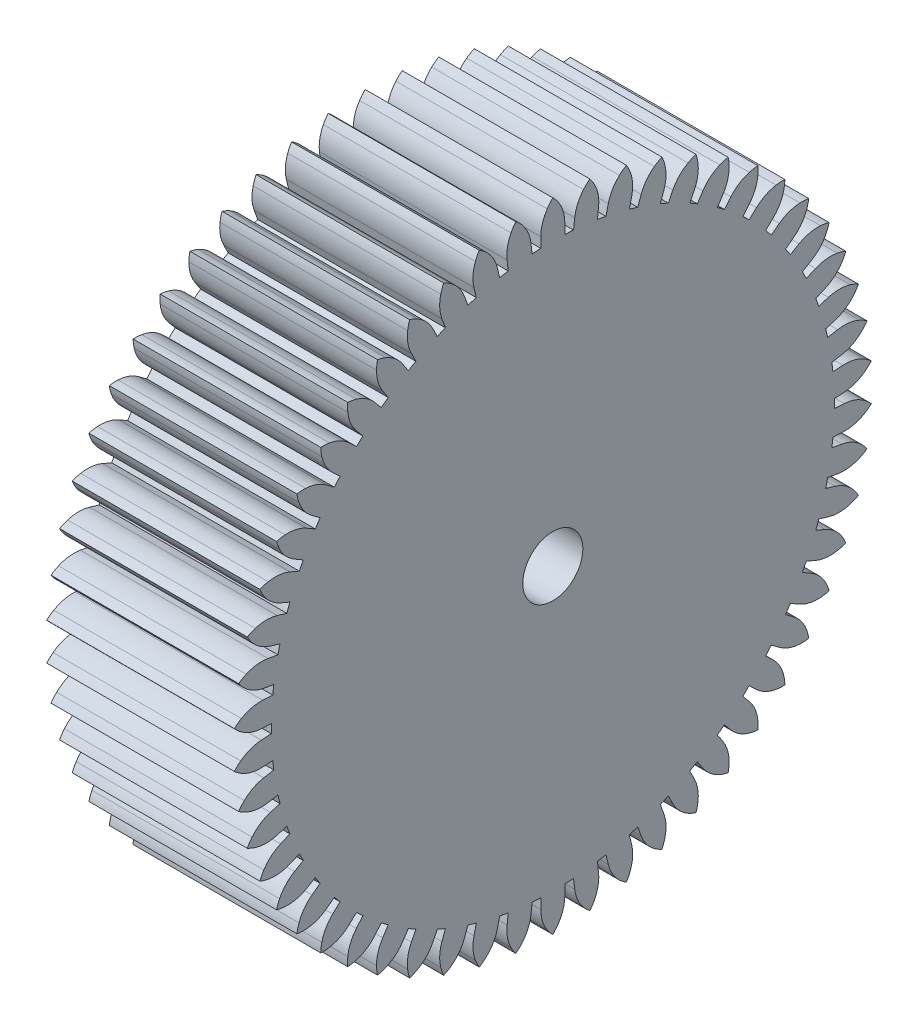
SolidWorks part; units mm, degrees
ref_plane "Front Plane" through (0, 0, 0) normal (0, 0, 1) x (1, 0, 0)
ref_plane "Top Plane" through (0, 0, 0) normal (0, 1, 0) x (1, 0, 0)
ref_plane "Right Plane" through (0, 0, 0) normal (1, 0, 0) x (0, 0, -1)
sketch "Sketch1" plane through (0, 0, 0) normal (1, 0, 0) x (0, 0, -1)
  line L0 (-0.64, 14.9863) -> (-0.64, 15.5242)
  line L1 (0, 18.7) -> (0, -18.7) construction
  line L2 (0, 17) -> (0, 15)
  line L3 (0.64, 14.9863) -> (0.64, 15.5242)
  line L4 (1.1041, 14.9593) -> (1.1666, 15.4936)
  line L5 (2.3755, 14.8107) -> (2.4379, 15.345)
  line L6 (2.8333, 14.73) -> (2.9574, 15.2534)
  line L7 (4.0788, 14.4348) -> (4.2029, 14.9582)
  line L8 (4.5242, 14.3014) -> (4.7082, 14.8069)
  line L9 (5.727, 13.8637) -> (5.911, 14.3691)
  line L10 (6.1539, 13.6795) -> (6.3953, 14.1602)
  line L11 (7.2978, 13.1051) -> (7.5392, 13.5857)
  line L12 (7.7004, 12.8726) -> (7.996, 13.322)
  line L13 (8.7698, 12.1692) -> (9.0654, 12.6186)
  line L14 (9.1428, 11.8916) -> (9.4885, 12.3036)
  line L15 (10.1233, 11.0688) -> (10.469, 11.4809)
  line L16 (10.4615, 10.7498) -> (10.8527, 11.1189)
  line L17 (11.3399, 9.8187) -> (11.7311, 10.1878)
  line L18 (11.6387, 9.4626) -> (12.0702, 9.7838)
  line L19 (12.4031, 8.4359) -> (12.8345, 8.7571)
  line L20 (12.6586, 8.0474) -> (13.1244, 8.3164)
  line L21 (13.2986, 6.9389) -> (13.7644, 7.2079)
  line L22 (13.5072, 6.5234) -> (14.0011, 6.7365)
  line L23 (14.0142, 5.3481) -> (14.5081, 5.5612)
  line L24 (14.1732, 4.9112) -> (14.6885, 5.0655)
  line L25 (14.5403, 3.685) -> (15.0556, 3.8393)
  line L26 (14.6475, 3.2326) -> (15.1772, 3.326)
  line L27 (14.8698, 1.9721) -> (15.3995, 2.0655)
  line L28 (14.9238, 1.5103) -> (15.4607, 1.5416)
  line L29 (14.9982, 0.2325) -> (15.5352, 0.2637)
  line L30 (14.9982, -0.2325) -> (15.5352, -0.2637)
  line L31 (14.9238, -1.5103) -> (15.4607, -1.5416)
  line L32 (14.8698, -1.9721) -> (15.3995, -2.0655)
  line L33 (14.6475, -3.2326) -> (15.1772, -3.326)
  line L34 (14.5403, -3.685) -> (15.0556, -3.8393)
  line L35 (14.1732, -4.9112) -> (14.6885, -5.0655)
  line L36 (14.0142, -5.3481) -> (14.5081, -5.5612)
  line L37 (13.5072, -6.5234) -> (14.0011, -6.7365)
  line L38 (13.2986, -6.9389) -> (13.7644, -7.2079)
  line L39 (12.6586, -8.0474) -> (13.1244, -8.3164)
  line L40 (12.4031, -8.4359) -> (12.8345, -8.7571)
  line L41 (11.6387, -9.4626) -> (12.0702, -9.7838)
  line L42 (11.3399, -9.8187) -> (11.7311, -10.1878)
  line L43 (10.4615, -10.7498) -> (10.8527, -11.1189)
  line L44 (10.1233, -11.0688) -> (10.469, -11.4809)
  line L45 (9.1428, -11.8916) -> (9.4885, -12.3036)
  line L46 (8.7698, -12.1692) -> (9.0654, -12.6186)
  line L47 (7.7004, -12.8726) -> (7.996, -13.322)
  line L48 (7.2978, -13.1051) -> (7.5392, -13.5857)
  line L49 (6.1539, -13.6795) -> (6.3953, -14.1602)
  line L50 (5.727, -13.8637) -> (5.911, -14.3691)
  line L51 (4.5242, -14.3014) -> (4.7082, -14.8069)
  line L52 (4.0788, -14.4348) -> (4.2029, -14.9582)
  line L53 (2.8333, -14.73) -> (2.9574, -15.2534)
  line L54 (2.3755, -14.8107) -> (2.4379, -15.345)
  line L55 (1.1041, -14.9593) -> (1.1666, -15.4936)
  line L56 (0.64, -14.9863) -> (0.64, -15.5242)
  line L57 (-0.64, -14.9863) -> (-0.64, -15.5242)
  line L58 (-1.1041, -14.9593) -> (-1.1666, -15.4936)
  line L59 (-2.3755, -14.8107) -> (-2.4379, -15.345)
  line L60 (-2.8333, -14.73) -> (-2.9574, -15.2534)
  line L61 (-4.0788, -14.4348) -> (-4.2029, -14.9582)
  line L62 (-4.5242, -14.3014) -> (-4.7082, -14.8069)
  line L63 (-5.727, -13.8637) -> (-5.911, -14.3691)
  line L64 (-6.1539, -13.6795) -> (-6.3953, -14.1602)
  line L65 (-7.2978, -13.1051) -> (-7.5392, -13.5857)
  line L66 (-7.7004, -12.8726) -> (-7.996, -13.322)
  line L67 (-8.7698, -12.1692) -> (-9.0654, -12.6186)
  line L68 (-9.1428, -11.8916) -> (-9.4885, -12.3036)
  line L69 (-10.1233, -11.0688) -> (-10.469, -11.4809)
  line L70 (-10.4615, -10.7498) -> (-10.8527, -11.1189)
  line L71 (-11.3399, -9.8187) -> (-11.7311, -10.1878)
  line L72 (-11.6387, -9.4626) -> (-12.0702, -9.7838)
  line L73 (-12.4031, -8.4359) -> (-12.8345, -8.7571)
  line L74 (-12.6586, -8.0474) -> (-13.1244, -8.3164)
  line L75 (-13.2986, -6.9389) -> (-13.7644, -7.2079)
  line L76 (-13.5072, -6.5234) -> (-14.0011, -6.7365)
  line L77 (-14.0142, -5.3481) -> (-14.5081, -5.5612)
  line L78 (-14.1732, -4.9112) -> (-14.6885, -5.0655)
  line L79 (-14.5403, -3.685) -> (-15.0556, -3.8393)
  line L80 (-14.6475, -3.2326) -> (-15.1772, -3.326)
  line L81 (-14.8698, -1.9721) -> (-15.3995, -2.0655)
  line L82 (-14.9238, -1.5103) -> (-15.4607, -1.5416)
  line L83 (-14.9982, -0.2325) -> (-15.5352, -0.2637)
  line L84 (-14.9982, 0.2325) -> (-15.5352, 0.2637)
  line L85 (-14.9238, 1.5103) -> (-15.4607, 1.5416)
  line L86 (-14.8698, 1.9721) -> (-15.3995, 2.0655)
  line L87 (-14.6475, 3.2326) -> (-15.1772, 3.326)
  line L88 (-14.5403, 3.685) -> (-15.0556, 3.8393)
  line L89 (-14.1732, 4.9112) -> (-14.6885, 5.0655)
  line L90 (-14.0142, 5.3481) -> (-14.5081, 5.5612)
  line L91 (-13.5072, 6.5234) -> (-14.0011, 6.7365)
  line L92 (-13.2986, 6.9389) -> (-13.7644, 7.2079)
  line L93 (-12.6586, 8.0474) -> (-13.1244, 8.3164)
  line L94 (-12.4031, 8.4359) -> (-12.8345, 8.7571)
  line L95 (-11.6387, 9.4626) -> (-12.0702, 9.7838)
  line L96 (-11.3399, 9.8187) -> (-11.7311, 10.1878)
  line L97 (-10.4615, 10.7498) -> (-10.8527, 11.1189)
  line L98 (-10.1233, 11.0688) -> (-10.469, 11.4809)
  line L99 (-9.1428, 11.8916) -> (-9.4885, 12.3036)
  line L100 (-8.7698, 12.1692) -> (-9.0654, 12.6186)
  line L101 (-7.7004, 12.8726) -> (-7.996, 13.322)
  line L102 (-7.2978, 13.1051) -> (-7.5392, 13.5857)
  line L103 (-6.1539, 13.6795) -> (-6.3953, 14.1602)
  line L104 (-5.727, 13.8637) -> (-5.911, 14.3691)
  line L105 (-4.5242, 14.3014) -> (-4.7082, 14.8069)
  line L106 (-4.0788, 14.4348) -> (-4.2029, 14.9582)
  line L107 (-2.8333, 14.73) -> (-2.9574, 15.2534)
  line L108 (-2.3755, 14.8107) -> (-2.4379, 15.345)
  line L109 (-1.1041, 14.9593) -> (-1.1666, 15.4936)
  arc A0 (-0.64, 14.9863) -> (-1.1041, 14.9593) centre (0, 0) ccw
  arc A2 (-0.64, 15.5242) -> (-0.2982, 16.6425) centre (1.36, 15.5242) cw
  arc A3 (-0.2982, 16.6425) -> (0, 17) centre (1.6012, 15.3616) cw
  arc A4 (0.64, 15.5242) -> (0.2982, 16.6425) centre (-1.36, 15.5242) ccw
  arc A5 (0.2982, 16.6425) -> (0, 17) centre (-1.6012, 15.3616) ccw
  arc A6 (2.4379, 15.345) -> (2.2282, 16.4953) centre (0.4514, 15.5771) ccw
  arc A7 (2.2282, 16.4953) -> (1.9736, 16.8851) centre (0.193, 15.4436) ccw
  arc A8 (1.6359, 16.5646) -> (1.9736, 16.8851) centre (3.3737, 15.0718) cw
  arc A9 (1.1666, 15.4936) -> (1.6359, 16.5646) centre (3.1531, 15.2614) cw
  arc A10 (4.2029, 14.9582) -> (4.1281, 16.1251) centre (2.2568, 15.4194) ccw
  arc A11 (4.1281, 16.1251) -> (3.9205, 16.5418) centre (1.9846, 15.3168) ccw
  arc A12 (3.5479, 16.2626) -> (3.9205, 16.5418) centre (5.1006, 14.5783) cw
  arc A13 (2.9574, 15.2534) -> (3.5479, 16.2626) centre (4.9035, 14.7921) cw
  arc A14 (5.911, 14.3691) -> (5.9722, 15.5368) centre (4.0316, 15.0531) ccw
  arc A15 (5.9722, 15.5368) -> (5.8143, 15.9748) centre (3.7494, 14.9828) ccw
  arc A16 (5.4119, 15.7408) -> (5.8143, 15.9748) centre (6.7586, 13.8875) cw
  arc A17 (4.7082, 14.8069) -> (5.4119, 15.7408) centre (6.5876, 14.1228) cw
  arc A18 (7.5392, 13.5857) -> (7.7356, 14.7384) centre (5.7519, 14.4833) ccw
  arc A19 (7.7356, 14.7384) -> (7.6296, 15.1918) centre (5.4634, 14.4462) ccw
  arc A20 (7.2027, 15.0061) -> (7.6296, 15.1918) centre (8.3251, 13.009) cw
  arc A21 (6.3953, 14.1602) -> (7.2027, 15.0061) centre (8.1826, 13.2626) cw
  arc A22 (9.0654, 12.6186) -> (9.3943, 13.7407) centre (7.3944, 13.7176) ccw
  arc A23 (9.3943, 13.7407) -> (9.3417, 14.2033) centre (7.1036, 13.7143) ccw
  arc A24 (8.8961, 14.0684) -> (9.3417, 14.2033) centre (9.7791, 11.9546) cw
  arc A25 (7.996, 13.322) -> (8.8961, 14.0684) centre (9.667, 12.223) cw
  arc A26 (10.469, 11.4809) -> (10.926, 12.5572) centre (8.937, 12.7664) ccw
  arc A27 (10.926, 12.5572) -> (10.9274, 13.0228) centre (8.6477, 12.7969) ccw
  arc A28 (10.4692, 12.9405) -> (10.9274, 13.0228) centre (11.1008, 10.7384) cw
  arc A29 (9.4885, 12.3036) -> (10.4692, 12.9405) centre (11.0206, 11.0181) cw
  arc A30 (11.7311, 10.1878) -> (12.3099, 11.2039) centre (10.3586, 11.6426) ccw
  arc A31 (12.3099, 11.2039) -> (12.3654, 11.6661) centre (10.0748, 11.7064) ccw
  arc A32 (11.9007, 11.6376) -> (12.3654, 11.6661) centre (12.2724, 9.3771) cw
  arc A33 (10.8527, 11.1189) -> (11.9007, 11.6376) centre (12.2252, 9.6641) cw
  arc A34 (12.8345, 8.7571) -> (13.5274, 9.699) centre (11.6402, 10.3613) ccw
  arc A35 (13.5274, 9.699) -> (13.6361, 10.1517) centre (11.3657, 10.4576) ccw
  arc A36 (13.1713, 10.1774) -> (13.6361, 10.1517) centre (13.278, 7.889) cw
  arc A37 (12.0702, 9.7838) -> (13.1713, 10.1774) centre (13.2645, 8.1795) cw
  arc A38 (13.7644, 7.2079) -> (14.5619, 8.063) centre (12.7644, 8.9399) ccw
  arc A39 (14.5619, 8.063) -> (14.7224, 8.5) centre (12.5029, 9.0674) ccw
  arc A40 (14.2637, 8.5795) -> (14.7224, 8.5) centre (14.1041, 6.2941) cw
  arc A41 (13.1244, 8.3164) -> (14.2637, 8.5795) centre (14.1244, 6.5843) cw
  arc A42 (14.5081, 5.5612) -> (15.3995, 6.318) centre (13.7159, 7.3976) ccw
  arc A43 (15.3995, 6.318) -> (15.6097, 6.7334) centre (13.4711, 7.5546) ccw
  arc A44 (15.1633, 6.8655) -> (15.6097, 6.7334) centre (14.7394, 4.6142) cw
  arc A45 (14.0011, 6.7365) -> (15.1633, 6.8655) centre (14.7933, 4.9001) cw
  arc A46 (15.0556, 3.8393) -> (16.0288, 4.4875) centre (14.482, 5.7553) ccw
  arc A47 (16.0288, 4.4875) -> (16.2858, 4.8757) centre (14.257, 5.9397) ccw
  arc A48 (15.8578, 5.0588) -> (16.2858, 4.8757) centre (15.1755, 2.8718) cw
  arc A49 (14.6885, 5.0655) -> (15.8578, 5.0588) centre (15.2621, 3.1495) cw
  arc A50 (15.3995, 2.0655) -> (16.4414, 2.5963) centre (15.0522, 4.0351) ccw
  arc A51 (16.4414, 2.5963) -> (16.7417, 2.952) centre (14.8502, 4.2444) ccw
  arc A52 (16.3379, 3.1836) -> (16.7417, 2.952) centre (15.4062, 1.0907) cw
  arc A53 (15.1772, 3.326) -> (16.3379, 3.1836) centre (15.5245, 1.3564) cw
  arc A54 (15.5352, 0.2637) -> (16.6316, 0.67) centre (15.4189, 2.2604) ccw
  arc A55 (16.6316, 0.67) -> (16.9712, 0.9885) centre (15.2425, 2.4917) ccw
  arc A56 (16.597, 1.2653) -> (16.9712, 0.9885) centre (15.4287, -0.7053) cw
  arc A57 (15.4607, 1.5416) -> (16.597, 1.2653) centre (15.577, -0.455) cw
  arc A58 (15.4607, -1.5416) -> (16.597, -1.2653) centre (15.577, 0.455) ccw
  arc A59 (16.597, -1.2653) -> (16.9712, -0.9885) centre (15.4287, 0.7053) ccw
  arc A60 (16.6316, -0.67) -> (16.9712, -0.9885) centre (15.2425, -2.4917) cw
  arc A61 (15.5352, -0.2637) -> (16.6316, -0.67) centre (15.4189, -2.2604) cw
  arc A62 (15.1772, -3.326) -> (16.3379, -3.1836) centre (15.5245, -1.3564) ccw
  arc A63 (16.3379, -3.1836) -> (16.7417, -2.952) centre (15.4062, -1.0907) ccw
  arc A64 (16.4414, -2.5963) -> (16.7417, -2.952) centre (14.8502, -4.2444) cw
  arc A65 (15.3995, -2.0655) -> (16.4414, -2.5963) centre (15.0522, -4.0351) cw
  arc A66 (14.6885, -5.0655) -> (15.8578, -5.0588) centre (15.2621, -3.1495) ccw
  arc A67 (15.8578, -5.0588) -> (16.2858, -4.8757) centre (15.1755, -2.8718) ccw
  arc A68 (16.0288, -4.4875) -> (16.2858, -4.8757) centre (14.257, -5.9397) cw
  arc A69 (15.0556, -3.8393) -> (16.0288, -4.4875) centre (14.482, -5.7553) cw
  arc A70 (14.0011, -6.7365) -> (15.1633, -6.8655) centre (14.7933, -4.9001) ccw
  arc A71 (15.1633, -6.8655) -> (15.6097, -6.7334) centre (14.7394, -4.6142) ccw
  arc A72 (15.3995, -6.318) -> (15.6097, -6.7334) centre (13.4711, -7.5546) cw
  arc A73 (14.5081, -5.5612) -> (15.3995, -6.318) centre (13.7159, -7.3976) cw
  arc A74 (13.1244, -8.3164) -> (14.2637, -8.5795) centre (14.1244, -6.5843) ccw
  arc A75 (14.2637, -8.5795) -> (14.7224, -8.5) centre (14.1041, -6.2941) ccw
  arc A76 (14.5619, -8.063) -> (14.7224, -8.5) centre (12.5029, -9.0674) cw
  arc A77 (13.7644, -7.2079) -> (14.5619, -8.063) centre (12.7644, -8.9399) cw
  arc A78 (12.0702, -9.7838) -> (13.1713, -10.1774) centre (13.2645, -8.1795) ccw
  arc A79 (13.1713, -10.1774) -> (13.6361, -10.1517) centre (13.278, -7.889) ccw
  arc A80 (13.5274, -9.699) -> (13.6361, -10.1517) centre (11.3657, -10.4576) cw
  arc A81 (12.8345, -8.7571) -> (13.5274, -9.699) centre (11.6402, -10.3613) cw
  arc A82 (10.8527, -11.1189) -> (11.9007, -11.6376) centre (12.2252, -9.6641) ccw
  arc A83 (11.9007, -11.6376) -> (12.3654, -11.6661) centre (12.2724, -9.3771) ccw
  arc A84 (12.3099, -11.2039) -> (12.3654, -11.6661) centre (10.0748, -11.7064) cw
  arc A85 (11.7311, -10.1878) -> (12.3099, -11.2039) centre (10.3586, -11.6426) cw
  arc A86 (9.4885, -12.3036) -> (10.4692, -12.9405) centre (11.0206, -11.0181) ccw
  arc A87 (10.4692, -12.9405) -> (10.9274, -13.0228) centre (11.1008, -10.7384) ccw
  arc A88 (10.926, -12.5572) -> (10.9274, -13.0228) centre (8.6477, -12.7969) cw
  arc A89 (10.469, -11.4809) -> (10.926, -12.5572) centre (8.937, -12.7664) cw
  arc A90 (7.996, -13.322) -> (8.8961, -14.0684) centre (9.667, -12.223) ccw
  arc A91 (8.8961, -14.0684) -> (9.3417, -14.2033) centre (9.7791, -11.9546) ccw
  arc A92 (9.3943, -13.7407) -> (9.3417, -14.2033) centre (7.1036, -13.7143) cw
  arc A93 (9.0654, -12.6186) -> (9.3943, -13.7407) centre (7.3944, -13.7176) cw
  arc A94 (6.3953, -14.1602) -> (7.2027, -15.0061) centre (8.1826, -13.2626) ccw
  arc A95 (7.2027, -15.0061) -> (7.6296, -15.1918) centre (8.3251, -13.009) ccw
  arc A96 (7.7356, -14.7384) -> (7.6296, -15.1918) centre (5.4634, -14.4462) cw
  arc A97 (7.5392, -13.5857) -> (7.7356, -14.7384) centre (5.7519, -14.4833) cw
  arc A98 (4.7082, -14.8069) -> (5.4119, -15.7408) centre (6.5876, -14.1228) ccw
  arc A99 (5.4119, -15.7408) -> (5.8143, -15.9748) centre (6.7586, -13.8875) ccw
  arc A100 (5.9722, -15.5368) -> (5.8143, -15.9748) centre (3.7494, -14.9828) cw
  arc A101 (5.911, -14.3691) -> (5.9722, -15.5368) centre (4.0316, -15.0531) cw
  arc A102 (2.9574, -15.2534) -> (3.5479, -16.2626) centre (4.9035, -14.7921) ccw
  arc A103 (3.5479, -16.2626) -> (3.9205, -16.5418) centre (5.1006, -14.5783) ccw
  arc A104 (4.1281, -16.1251) -> (3.9205, -16.5418) centre (1.9846, -15.3168) cw
  arc A105 (4.2029, -14.9582) -> (4.1281, -16.1251) centre (2.2568, -15.4194) cw
  arc A106 (1.1666, -15.4936) -> (1.6359, -16.5646) centre (3.1531, -15.2614) ccw
  arc A107 (1.6359, -16.5646) -> (1.9736, -16.8851) centre (3.3737, -15.0718) ccw
  arc A108 (2.2282, -16.4953) -> (1.9736, -16.8851) centre (0.193, -15.4436) cw
  arc A109 (2.4379, -15.345) -> (2.2282, -16.4953) centre (0.4514, -15.5771) cw
  arc A110 (-0.64, -15.5242) -> (-0.2982, -16.6425) centre (1.36, -15.5242) ccw
  arc A111 (-0.2982, -16.6425) -> (0, -17) centre (1.6012, -15.3616) ccw
  arc A112 (0.2982, -16.6425) -> (0, -17) centre (-1.6012, -15.3616) cw
  arc A113 (0.64, -15.5242) -> (0.2982, -16.6425) centre (-1.36, -15.5242) cw
  arc A114 (-2.4379, -15.345) -> (-2.2282, -16.4953) centre (-0.4514, -15.5771) ccw
  arc A115 (-2.2282, -16.4953) -> (-1.9736, -16.8851) centre (-0.193, -15.4436) ccw
  arc A116 (-1.6359, -16.5646) -> (-1.9736, -16.8851) centre (-3.3737, -15.0718) cw
  arc A117 (-1.1666, -15.4936) -> (-1.6359, -16.5646) centre (-3.1531, -15.2614) cw
  arc A118 (-4.2029, -14.9582) -> (-4.1281, -16.1251) centre (-2.2568, -15.4194) ccw
  arc A119 (-4.1281, -16.1251) -> (-3.9205, -16.5418) centre (-1.9846, -15.3168) ccw
  arc A120 (-3.5479, -16.2626) -> (-3.9205, -16.5418) centre (-5.1006, -14.5783) cw
  arc A121 (-2.9574, -15.2534) -> (-3.5479, -16.2626) centre (-4.9035, -14.7921) cw
  arc A122 (-5.911, -14.3691) -> (-5.9722, -15.5368) centre (-4.0316, -15.0531) ccw
  arc A123 (-5.9722, -15.5368) -> (-5.8143, -15.9748) centre (-3.7494, -14.9828) ccw
  arc A124 (-5.4119, -15.7408) -> (-5.8143, -15.9748) centre (-6.7586, -13.8875) cw
  arc A125 (-4.7082, -14.8069) -> (-5.4119, -15.7408) centre (-6.5876, -14.1228) cw
  arc A126 (-7.5392, -13.5857) -> (-7.7356, -14.7384) centre (-5.7519, -14.4833) ccw
  arc A127 (-7.7356, -14.7384) -> (-7.6296, -15.1918) centre (-5.4634, -14.4462) ccw
  arc A128 (-7.2027, -15.0061) -> (-7.6296, -15.1918) centre (-8.3251, -13.009) cw
  arc A129 (-6.3953, -14.1602) -> (-7.2027, -15.0061) centre (-8.1826, -13.2626) cw
  arc A130 (-9.0654, -12.6186) -> (-9.3943, -13.7407) centre (-7.3944, -13.7176) ccw
  arc A131 (-9.3943, -13.7407) -> (-9.3417, -14.2033) centre (-7.1036, -13.7143) ccw
  arc A132 (-8.8961, -14.0684) -> (-9.3417, -14.2033) centre (-9.7791, -11.9546) cw
  arc A133 (-7.996, -13.322) -> (-8.8961, -14.0684) centre (-9.667, -12.223) cw
  arc A134 (-10.469, -11.4809) -> (-10.926, -12.5572) centre (-8.937, -12.7664) ccw
  arc A135 (-10.926, -12.5572) -> (-10.9274, -13.0228) centre (-8.6477, -12.7969) ccw
  arc A136 (-10.4692, -12.9405) -> (-10.9274, -13.0228) centre (-11.1008, -10.7384) cw
  arc A137 (-9.4885, -12.3036) -> (-10.4692, -12.9405) centre (-11.0206, -11.0181) cw
  arc A138 (-11.7311, -10.1878) -> (-12.3099, -11.2039) centre (-10.3586, -11.6426) ccw
  arc A139 (-12.3099, -11.2039) -> (-12.3654, -11.6661) centre (-10.0748, -11.7064) ccw
  arc A140 (-11.9007, -11.6376) -> (-12.3654, -11.6661) centre (-12.2724, -9.3771) cw
  arc A141 (-10.8527, -11.1189) -> (-11.9007, -11.6376) centre (-12.2252, -9.6641) cw
  arc A142 (-12.8345, -8.7571) -> (-13.5274, -9.699) centre (-11.6402, -10.3613) ccw
  arc A143 (-13.5274, -9.699) -> (-13.6361, -10.1517) centre (-11.3657, -10.4576) ccw
  arc A144 (-13.1713, -10.1774) -> (-13.6361, -10.1517) centre (-13.278, -7.889) cw
  arc A145 (-12.0702, -9.7838) -> (-13.1713, -10.1774) centre (-13.2645, -8.1795) cw
  arc A146 (-13.7644, -7.2079) -> (-14.5619, -8.063) centre (-12.7644, -8.9399) ccw
  arc A147 (-14.5619, -8.063) -> (-14.7224, -8.5) centre (-12.5029, -9.0674) ccw
  arc A148 (-14.2637, -8.5795) -> (-14.7224, -8.5) centre (-14.1041, -6.2941) cw
  arc A149 (-13.1244, -8.3164) -> (-14.2637, -8.5795) centre (-14.1244, -6.5843) cw
  arc A150 (-14.5081, -5.5612) -> (-15.3995, -6.318) centre (-13.7159, -7.3976) ccw
  arc A151 (-15.3995, -6.318) -> (-15.6097, -6.7334) centre (-13.4711, -7.5546) ccw
  arc A152 (-15.1633, -6.8655) -> (-15.6097, -6.7334) centre (-14.7394, -4.6142) cw
  arc A153 (-14.0011, -6.7365) -> (-15.1633, -6.8655) centre (-14.7933, -4.9001) cw
  arc A154 (-15.0556, -3.8393) -> (-16.0288, -4.4875) centre (-14.482, -5.7553) ccw
  arc A155 (-16.0288, -4.4875) -> (-16.2858, -4.8757) centre (-14.257, -5.9397) ccw
  arc A156 (-15.8578, -5.0588) -> (-16.2858, -4.8757) centre (-15.1755, -2.8718) cw
  arc A157 (-14.6885, -5.0655) -> (-15.8578, -5.0588) centre (-15.2621, -3.1495) cw
  arc A158 (-15.3995, -2.0655) -> (-16.4414, -2.5963) centre (-15.0522, -4.0351) ccw
  arc A159 (-16.4414, -2.5963) -> (-16.7417, -2.952) centre (-14.8502, -4.2444) ccw
  arc A160 (-16.3379, -3.1836) -> (-16.7417, -2.952) centre (-15.4062, -1.0907) cw
  arc A161 (-15.1772, -3.326) -> (-16.3379, -3.1836) centre (-15.5245, -1.3564) cw
  arc A162 (-15.5352, -0.2637) -> (-16.6316, -0.67) centre (-15.4189, -2.2604) ccw
  arc A163 (-16.6316, -0.67) -> (-16.9712, -0.9885) centre (-15.2425, -2.4917) ccw
  arc A164 (-16.597, -1.2653) -> (-16.9712, -0.9885) centre (-15.4287, 0.7053) cw
  arc A165 (-15.4607, -1.5416) -> (-16.597, -1.2653) centre (-15.577, 0.455) cw
  arc A166 (-15.4607, 1.5416) -> (-16.597, 1.2653) centre (-15.577, -0.455) ccw
  arc A167 (-16.597, 1.2653) -> (-16.9712, 0.9885) centre (-15.4287, -0.7053) ccw
  arc A168 (-16.6316, 0.67) -> (-16.9712, 0.9885) centre (-15.2425, 2.4917) cw
  arc A169 (-15.5352, 0.2637) -> (-16.6316, 0.67) centre (-15.4189, 2.2604) cw
  arc A170 (-15.1772, 3.326) -> (-16.3379, 3.1836) centre (-15.5245, 1.3564) ccw
  arc A171 (-16.3379, 3.1836) -> (-16.7417, 2.952) centre (-15.4062, 1.0907) ccw
  arc A172 (-16.4414, 2.5963) -> (-16.7417, 2.952) centre (-14.8502, 4.2444) cw
  arc A173 (-15.3995, 2.0655) -> (-16.4414, 2.5963) centre (-15.0522, 4.0351) cw
  arc A174 (-14.6885, 5.0655) -> (-15.8578, 5.0588) centre (-15.2621, 3.1495) ccw
  arc A175 (-15.8578, 5.0588) -> (-16.2858, 4.8757) centre (-15.1755, 2.8718) ccw
  arc A176 (-16.0288, 4.4875) -> (-16.2858, 4.8757) centre (-14.257, 5.9397) cw
  arc A177 (-15.0556, 3.8393) -> (-16.0288, 4.4875) centre (-14.482, 5.7553) cw
  arc A178 (-14.0011, 6.7365) -> (-15.1633, 6.8655) centre (-14.7933, 4.9001) ccw
  arc A179 (-15.1633, 6.8655) -> (-15.6097, 6.7334) centre (-14.7394, 4.6142) ccw
  arc A180 (-15.3995, 6.318) -> (-15.6097, 6.7334) centre (-13.4711, 7.5546) cw
  arc A181 (-14.5081, 5.5612) -> (-15.3995, 6.318) centre (-13.7159, 7.3976) cw
  arc A182 (-13.1244, 8.3164) -> (-14.2637, 8.5795) centre (-14.1244, 6.5843) ccw
  arc A183 (-14.2637, 8.5795) -> (-14.7224, 8.5) centre (-14.1041, 6.2941) ccw
  arc A184 (-14.5619, 8.063) -> (-14.7224, 8.5) centre (-12.5029, 9.0674) cw
  arc A185 (-13.7644, 7.2079) -> (-14.5619, 8.063) centre (-12.7644, 8.9399) cw
  arc A186 (-12.0702, 9.7838) -> (-13.1713, 10.1774) centre (-13.2645, 8.1795) ccw
  arc A187 (-13.1713, 10.1774) -> (-13.6361, 10.1517) centre (-13.278, 7.889) ccw
  arc A188 (-13.5274, 9.699) -> (-13.6361, 10.1517) centre (-11.3657, 10.4576) cw
  arc A189 (-12.8345, 8.7571) -> (-13.5274, 9.699) centre (-11.6402, 10.3613) cw
  arc A190 (-10.8527, 11.1189) -> (-11.9007, 11.6376) centre (-12.2252, 9.6641) ccw
  arc A191 (-11.9007, 11.6376) -> (-12.3654, 11.6661) centre (-12.2724, 9.3771) ccw
  arc A192 (-12.3099, 11.2039) -> (-12.3654, 11.6661) centre (-10.0748, 11.7064) cw
  arc A193 (-11.7311, 10.1878) -> (-12.3099, 11.2039) centre (-10.3586, 11.6426) cw
  arc A194 (-9.4885, 12.3036) -> (-10.4692, 12.9405) centre (-11.0206, 11.0181) ccw
  arc A195 (-10.4692, 12.9405) -> (-10.9274, 13.0228) centre (-11.1008, 10.7384) ccw
  arc A196 (-10.926, 12.5572) -> (-10.9274, 13.0228) centre (-8.6477, 12.7969) cw
  arc A197 (-10.469, 11.4809) -> (-10.926, 12.5572) centre (-8.937, 12.7664) cw
  arc A198 (-7.996, 13.322) -> (-8.8961, 14.0684) centre (-9.667, 12.223) ccw
  arc A199 (-8.8961, 14.0684) -> (-9.3417, 14.2033) centre (-9.7791, 11.9546) ccw
  arc A200 (-9.3943, 13.7407) -> (-9.3417, 14.2033) centre (-7.1036, 13.7143) cw
  arc A201 (-9.0654, 12.6186) -> (-9.3943, 13.7407) centre (-7.3944, 13.7176) cw
  arc A202 (-6.3953, 14.1602) -> (-7.2027, 15.0061) centre (-8.1826, 13.2626) ccw
  arc A203 (-7.2027, 15.0061) -> (-7.6296, 15.1918) centre (-8.3251, 13.009) ccw
  arc A204 (-7.7356, 14.7384) -> (-7.6296, 15.1918) centre (-5.4634, 14.4462) cw
  arc A205 (-7.5392, 13.5857) -> (-7.7356, 14.7384) centre (-5.7519, 14.4833) cw
  arc A206 (-4.7082, 14.8069) -> (-5.4119, 15.7408) centre (-6.5876, 14.1228) ccw
  arc A207 (-5.4119, 15.7408) -> (-5.8143, 15.9748) centre (-6.7586, 13.8875) ccw
  arc A208 (-5.9722, 15.5368) -> (-5.8143, 15.9748) centre (-3.7494, 14.9828) cw
  arc A209 (-5.911, 14.3691) -> (-5.9722, 15.5368) centre (-4.0316, 15.0531) cw
  arc A210 (-2.9574, 15.2534) -> (-3.5479, 16.2626) centre (-4.9035, 14.7921) ccw
  arc A211 (-3.5479, 16.2626) -> (-3.9205, 16.5418) centre (-5.1006, 14.5783) ccw
  arc A212 (-4.1281, 16.1251) -> (-3.9205, 16.5418) centre (-1.9846, 15.3168) cw
  arc A213 (-4.2029, 14.9582) -> (-4.1281, 16.1251) centre (-2.2568, 15.4194) cw
  arc A214 (-1.1666, 15.4936) -> (-1.6359, 16.5646) centre (-3.1531, 15.2614) ccw
  arc A215 (-1.6359, 16.5646) -> (-1.9736, 16.8851) centre (-3.3737, 15.0718) ccw
  arc A216 (-2.2282, 16.4953) -> (-1.9736, 16.8851) centre (-0.193, 15.4436) cw
  arc A217 (-2.4379, 15.345) -> (-2.2282, 16.4953) centre (-0.4514, 15.5771) cw
  arc A218 (1.1041, 14.9593) -> (0.64, 14.9863) centre (0, 0) ccw
  arc A219 (2.8333, 14.73) -> (2.3755, 14.8107) centre (0, 0) ccw
  arc A220 (-2.3755, 14.8107) -> (-2.8333, 14.73) centre (0, 0) ccw
  arc A221 (-4.0788, 14.4348) -> (-4.5242, 14.3014) centre (0, 0) ccw
  arc A222 (-5.727, 13.8637) -> (-6.1539, 13.6795) centre (0, 0) ccw
  arc A223 (-7.2978, 13.1051) -> (-7.7004, 12.8726) centre (0, 0) ccw
  arc A224 (-8.7698, 12.1692) -> (-9.1428, 11.8916) centre (0, 0) ccw
  arc A225 (-10.1233, 11.0688) -> (-10.4615, 10.7498) centre (0, 0) ccw
  arc A226 (-11.3399, 9.8187) -> (-11.6387, 9.4626) centre (0, 0) ccw
  arc A227 (-12.4031, 8.4359) -> (-12.6586, 8.0474) centre (0, 0) ccw
  arc A228 (-13.2986, 6.9389) -> (-13.5072, 6.5234) centre (0, 0) ccw
  arc A229 (-14.0142, 5.3481) -> (-14.1732, 4.9112) centre (0, 0) ccw
  arc A230 (-14.5403, 3.685) -> (-14.6475, 3.2326) centre (0, 0) ccw
  arc A231 (-14.8698, 1.9721) -> (-14.9238, 1.5103) centre (0, 0) ccw
  arc A232 (-14.9982, 0.2325) -> (-14.9982, -0.2325) centre (0, 0) ccw
  arc A233 (-14.9238, -1.5103) -> (-14.8698, -1.9721) centre (0, 0) ccw
  arc A234 (-14.6475, -3.2326) -> (-14.5403, -3.685) centre (0, 0) ccw
  arc A235 (-14.1732, -4.9112) -> (-14.0142, -5.3481) centre (0, 0) ccw
  arc A236 (-13.5072, -6.5234) -> (-13.2986, -6.9389) centre (0, 0) ccw
  arc A237 (-12.6586, -8.0474) -> (-12.4031, -8.4359) centre (0, 0) ccw
  arc A238 (-11.6387, -9.4626) -> (-11.3399, -9.8187) centre (0, 0) ccw
  arc A239 (-10.4615, -10.7498) -> (-10.1233, -11.0688) centre (0, 0) ccw
  arc A240 (-9.1428, -11.8916) -> (-8.7698, -12.1692) centre (0, 0) ccw
  arc A241 (-7.7004, -12.8726) -> (-7.2978, -13.1051) centre (0, 0) ccw
  arc A242 (-6.1539, -13.6795) -> (-5.727, -13.8637) centre (0, 0) ccw
  arc A243 (-4.5242, -14.3014) -> (-4.0788, -14.4348) centre (0, 0) ccw
  arc A244 (-2.8333, -14.73) -> (-2.3755, -14.8107) centre (0, 0) ccw
  arc A245 (-1.1041, -14.9593) -> (-0.64, -14.9863) centre (0, 0) ccw
  arc A246 (0.64, -14.9863) -> (1.1041, -14.9593) centre (0, 0) ccw
  arc A247 (2.3755, -14.8107) -> (2.8333, -14.73) centre (0, 0) ccw
  arc A248 (4.0788, -14.4348) -> (4.5242, -14.3014) centre (0, 0) ccw
  arc A249 (5.727, -13.8637) -> (6.1539, -13.6795) centre (0, 0) ccw
  arc A250 (7.2978, -13.1051) -> (7.7004, -12.8726) centre (0, 0) ccw
  arc A251 (8.7698, -12.1692) -> (9.1428, -11.8916) centre (0, 0) ccw
  arc A252 (10.1233, -11.0688) -> (10.4615, -10.7498) centre (0, 0) ccw
  arc A253 (11.3399, -9.8187) -> (11.6387, -9.4626) centre (0, 0) ccw
  arc A254 (12.4031, -8.4359) -> (12.6586, -8.0474) centre (0, 0) ccw
  arc A255 (13.2986, -6.9389) -> (13.5072, -6.5234) centre (0, 0) ccw
  arc A256 (14.0142, -5.3481) -> (14.1732, -4.9112) centre (0, 0) ccw
  arc A257 (14.5403, -3.685) -> (14.6475, -3.2326) centre (0, 0) ccw
  arc A258 (14.8698, -1.9721) -> (14.9238, -1.5103) centre (0, 0) ccw
  arc A259 (14.9982, -0.2325) -> (14.9982, 0.2325) centre (0, 0) ccw
  arc A260 (14.9238, 1.5103) -> (14.8698, 1.9721) centre (0, 0) ccw
  arc A261 (14.6475, 3.2326) -> (14.5403, 3.685) centre (0, 0) ccw
  arc A262 (14.1732, 4.9112) -> (14.0142, 5.3481) centre (0, 0) ccw
  arc A263 (13.5072, 6.5234) -> (13.2986, 6.9389) centre (0, 0) ccw
  arc A264 (4.5242, 14.3014) -> (4.0788, 14.4348) centre (0, 0) ccw
  arc A265 (6.1539, 13.6795) -> (5.727, 13.8637) centre (0, 0) ccw
  arc A266 (7.7004, 12.8726) -> (7.2978, 13.1051) centre (0, 0) ccw
  arc A267 (9.1428, 11.8916) -> (8.7698, 12.1692) centre (0, 0) ccw
  arc A268 (10.4615, 10.7498) -> (10.1233, 11.0688) centre (0, 0) ccw
  arc A269 (11.6387, 9.4626) -> (11.3399, 9.8187) centre (0, 0) ccw
  arc A270 (12.6586, 8.0474) -> (12.4031, 8.4359) centre (0, 0) ccw
  point P604 (0, 0)
  dimension "D3" = 30
  dimension "D1" = 1.28
  dimension "D2" = 2
  dimension "D5" = 54
extrude "Boss-Extrude1" add sketch "Sketch1" along normal blind 10 contours L20 A270 L19 A34 A35 A36 A37 L18 A269 L17 A30 A31 A32 A33 L16 A268 L15 A26 A27 A28 A29 L14 A267 L13 A22 A23 A24 A25 L12 A266 L11 A18 A19 A20 A21 L10 A265 L9 A14 A15 A16 A17 L8 A264 L7 A10 A11 A12 A13 L6 A219
sketch "Sketch2" plane through (10, 0, 0) normal (1, 0, 0) x (0, 0, -1)
  circle A0 centre (0, 0) radius 1.6
  dimension "D1" = 3.2
extrude "Cut-Extrude1" cut sketch "Sketch2" against normal through all
